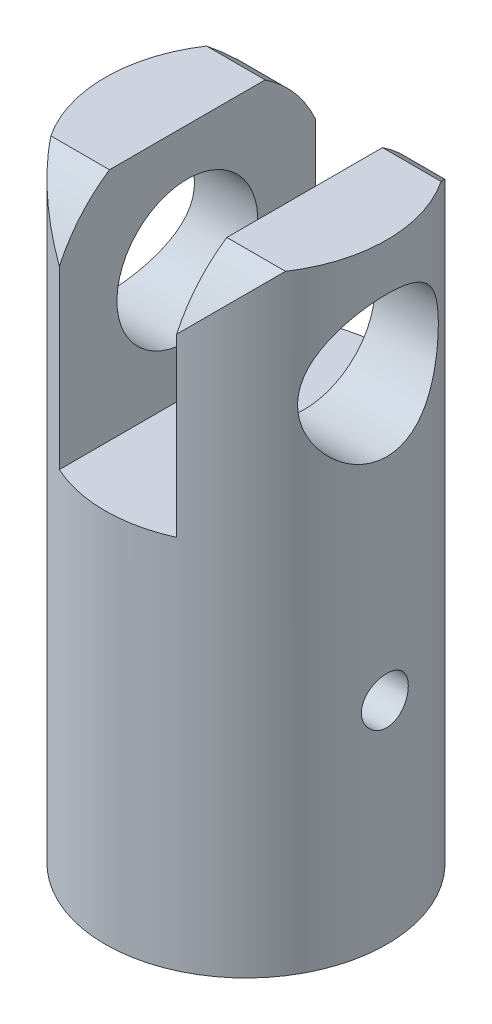
SolidWorks part; units mm, degrees
ref_plane "前视基准面" through (0, 0, 0) normal (0, 0, 1) x (1, 0, 0)
ref_plane "上视基准面" through (0, 0, 0) normal (0, 1, 0) x (1, 0, 0)
ref_plane "右视基准面" through (0, 0, 0) normal (1, 0, 0) x (0, 0, -1)
sketch "草图1" plane through (0, 0, 0) normal (0, 1, 0) x (1, 0, 0)
  circle A0 centre (0, 0) radius 3
  dimension "D1" = 6
extrude "凸台-拉伸1" add sketch "草图1" along normal blind 11
sketch "草图2" plane through (0, 0, 0) normal (0, -1, 0) x (1, 0, 0)
  circle A0 centre (0, 0) radius 1.5
  dimension "D1" = 3
extrude "切除-拉伸1" cut sketch "草图2" against normal blind 5
sketch "草图3" plane through (0, 0, 0) normal (1, 0, 0) x (0, 0, -1)
  line L0 (0, 11.5862) -> (0, -1.627) construction
  line L1 (3, 11) -> (-3, 11) construction
  line L2 (-3, 11) -> (-3, 0) construction
  line L4 (-3, 8.5) -> (-3, 11)
  line L5 (-3, 11) -> (-1.6582, 11.0001)
  line L6 (1.6582, 11.0001) -> (3, 11)
  line L7 (3, 11) -> (3, 8.5)
  line L8 (-3, 11) -> (3, 11) construction
  circle A0 centre (0, 8.5) radius 1.5
  arc A1 (-3, 8.5) -> (-1.6582, 11.0001) centre (0, 8.5) cw
  arc A2 (1.6582, 11.0001) -> (3, 8.5) centre (0, 8.5) cw
  circle A3 centre (0, 2.5) radius 0.5
  dimension "D1" = 3
  dimension "D3" = 3
  dimension "D4" = 1
  dimension "D2" = 2.5
  dimension "D5" = 2.5
extrude "切除-拉伸2" cut sketch "草图3" against normal through all both and the other way through all
sketch "草图4" plane through (0, 0, 0) normal (0, 0, 1) x (1, 0, 0)
  line L0 (0, 0) -> (0, 12.6545) construction
  line L1 (1.25, 6) -> (1.25, 11)
  line L2 (1.25, 6) -> (-1.25, 6)
  line L3 (1.25, 11) -> (-1.25, 11)
  line L4 (-1.25, 6) -> (-1.25, 11)
  line L5 (1.25, 6) -> (-1.25, 11) construction
  line L6 (1.25, 11) -> (-1.25, 6) construction
  line L7 (2.5, 11) -> (-2.5, 11) construction
  point P4 (0, 8.5)
  dimension "D1" = 2.5
  dimension "D2" = 5
extrude "切除-拉伸3" cut sketch "草图4" against normal through all both and the other way through all
sketch "草图5" plane through (0, 0, 0) normal (0, -1, 0) x (1, 0, 0)
  circle A0 centre (0, 0) radius 3
  circle A1 centre (0, 0) radius 1.5
  dimension "D1" = 3
  dimension "D2" = 6
extrude "凸台-拉伸2" add sketch "草图5" along normal blind 2
